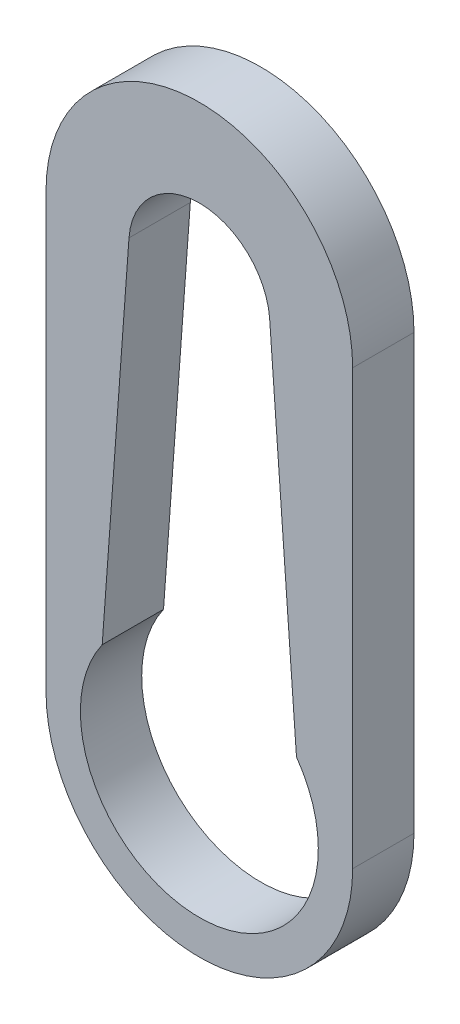
SolidWorks part; units mm, degrees
ref_plane "Front Plane" through (0, 0, 0) normal (0, 0, 1) x (1, 0, 0)
ref_plane "Top Plane" through (0, 0, 0) normal (0, 1, 0) x (1, 0, 0)
ref_plane "Right Plane" through (0, 0, 0) normal (1, 0, 0) x (0, 0, -1)
sketch "Sketch1" plane through (0, 0, 0) normal (0, 0, 1) x (1, 0, 0)
  line L0 (78.2916, 74.0996) -> (77.4175, 62.1716)
  line L1 (82.8793, 74.0996) -> (83.7534, 62.1716)
  line L3 (75.5854, 59.9315) -> (75.5854, 74.0776)
  line L5 (85.5854, 59.9315) -> (85.5854, 74.0776)
  arc A0 (75.5854, 74.0776) -> (85.5854, 74.0776) centre (80.5854, 74.0776) cw
  arc A1 (75.5854, 59.9315) -> (85.5854, 59.9315) centre (80.5854, 59.9315) ccw
  circle A2 centre (80.5854, 72.5315) radius 0.8
  circle A3 centre (80.5854, 59.9315) radius 1.85
  arc A5 (77.4175, 62.1716) -> (83.7534, 62.1716) centre (80.5854, 59.9324) ccw
  arc A6 (78.2916, 74.0996) -> (82.8793, 74.0996) centre (80.5854, 73.9315) cw
  point P21 (80.5854, 76.2315)
  point P23 (78.2916, 74.0996)
  point P26 (82.8793, 74.0996)
  point P27 (77.4175, 62.1716)
  point P28 (83.7534, 62.1716)
  point P29 (80.5854, 56.0529)
  point P30 (80.5854, 73.3315)
  dimension "D1" = 14.1462
  dimension "D2" = 10
  dimension "D4" = 2.9
extrude "Boss-Extrude1" add sketch "Sketch1" along normal blind 2 contours L3 A1 L5 A0 L0 A6 L1 A5
